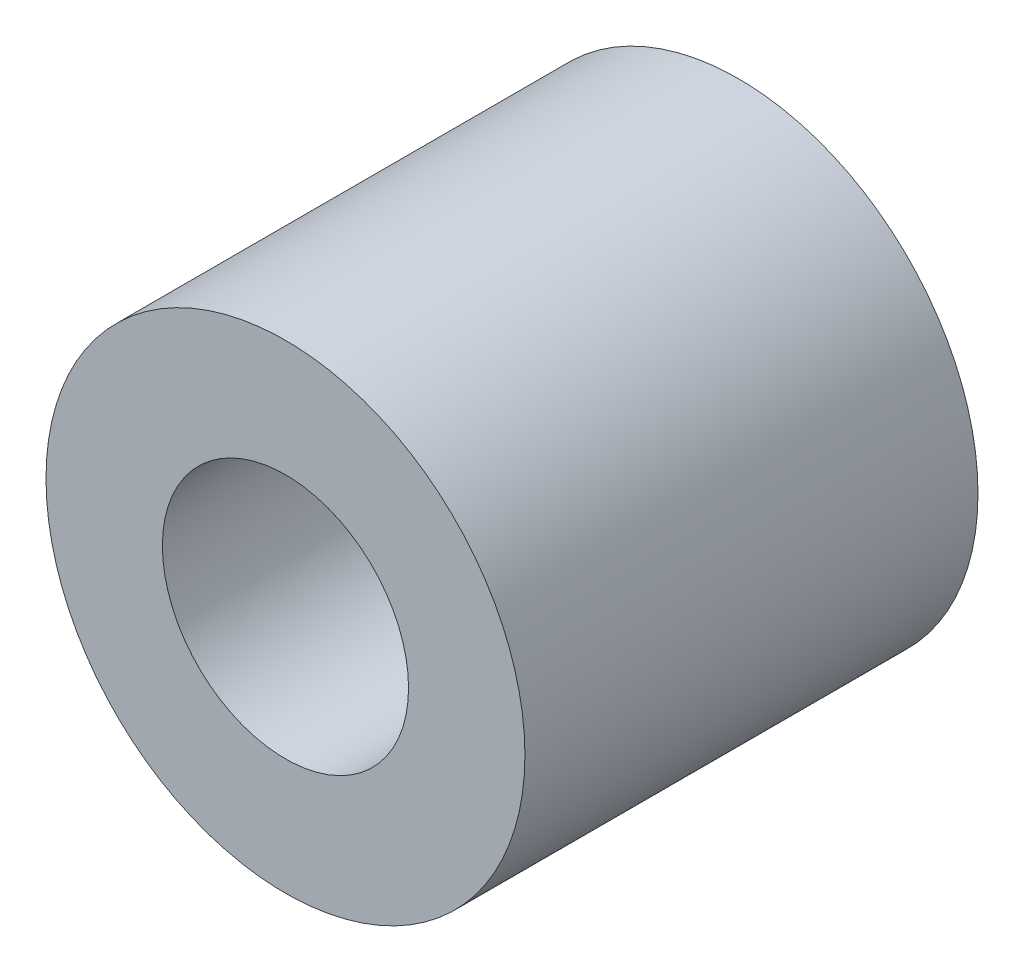
SolidWorks part; units mm, degrees
ref_plane "Front Plane" through (0, 0, 0) normal (0, 0, 1) x (1, 0, 0)
ref_plane "Top Plane" through (0, 0, 0) normal (0, 1, 0) x (1, 0, 0)
ref_plane "Right Plane" through (0, 0, 0) normal (1, 0, 0) x (0, 0, -1)
sketch "Sketch1" plane through (0, 0, 0) normal (0, 0, 1) x (1, 0, 0)
  circle A0 centre (0, 0) radius 3.2639
  circle A1 centre (0, 0) radius 6.35
  dimension "D1" = 12.7
  dimension "D2" = 6.5278
extrude "Boss-Extrude1" add sketch "Sketch1" along normal blind 12.0142
equation "\"OD\"= .5"
equation "\"ID\"= .257"
equation "\"L\"= .473"
equation "\"D1@Sketch1\"=\"OD\""
equation "\"D2@Sketch1\"=\"ID\""
equation "\"D1@Boss-Extrude1\"=\"L\""
